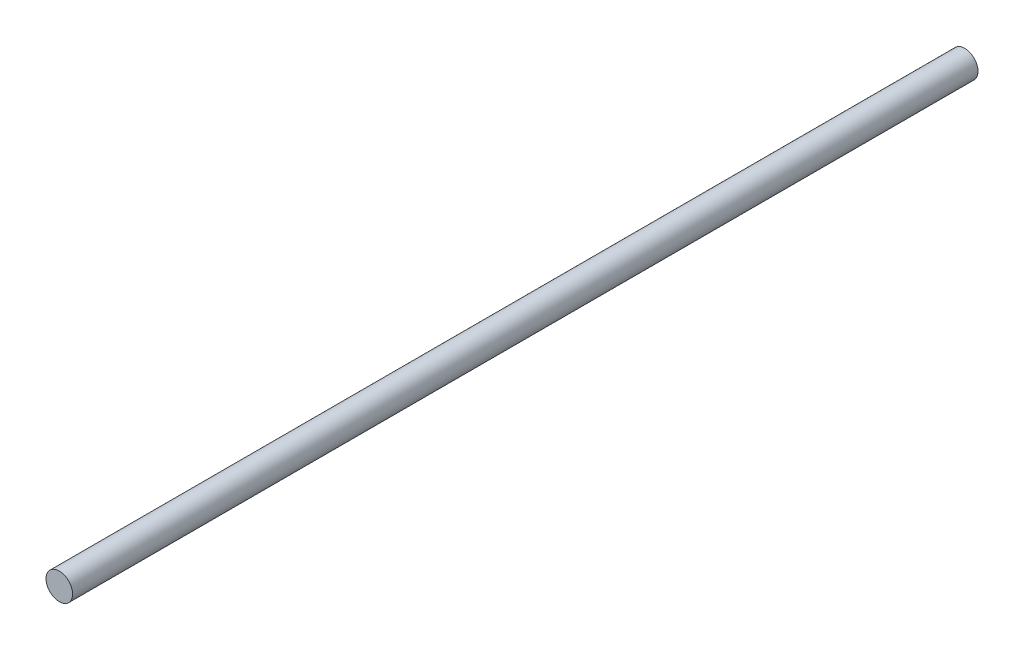
SolidWorks part; units mm, degrees
ref_plane "Front Plane" through (0, 0, 0) normal (0, 0, 1) x (1, 0, 0)
ref_plane "Top Plane" through (0, 0, 0) normal (0, 1, 0) x (1, 0, 0)
ref_plane "Right Plane" through (0, 0, 0) normal (1, 0, 0) x (0, 0, -1)
sketch "Sketch1" plane through (0, 0, 0) normal (0, 0, 1) x (1, 0, 0)
  circle A0 centre (0, 0) radius 6.35
  dimension "D1" = 12.7
extrude "Boss-Extrude1" add sketch "Sketch1" along normal blind 432.562
